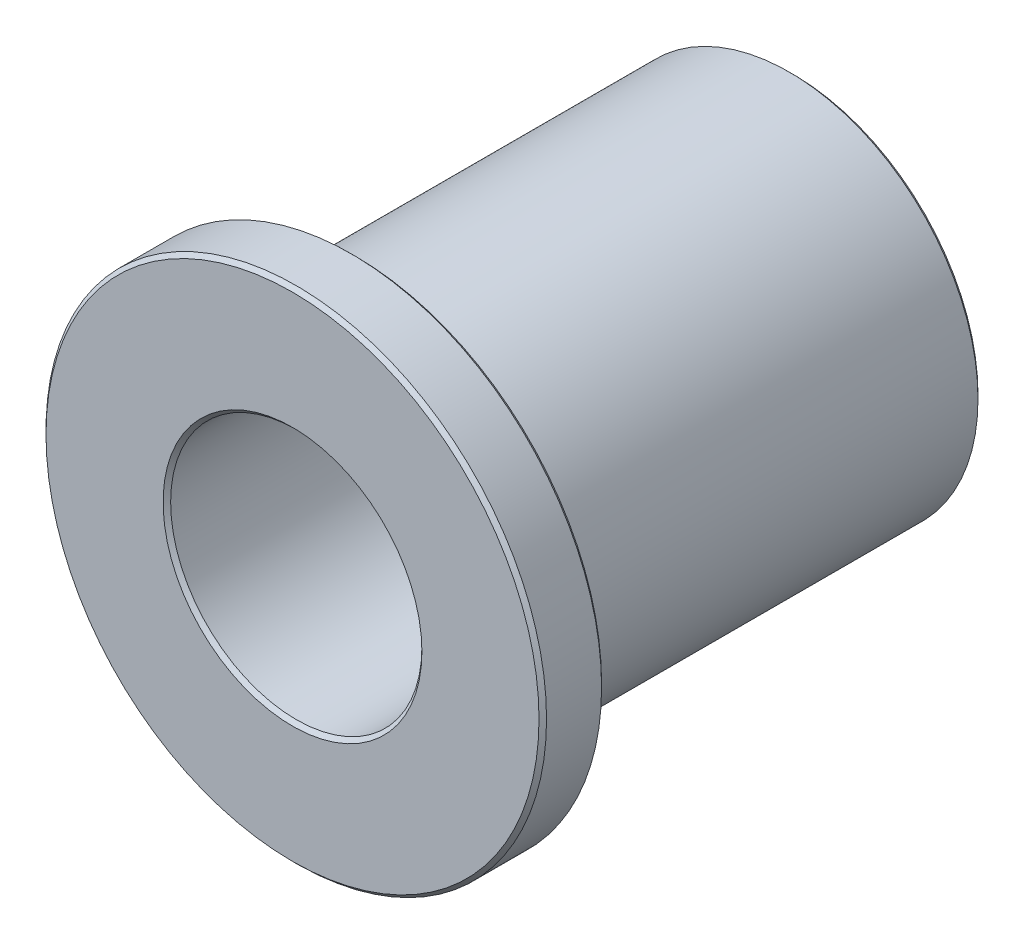
SolidWorks part; units mm, degrees
material "Brass"
ref_plane "Front" through (0, 0, 0) normal (0, 0, 1) x (1, 0, 0)
ref_plane "Top" through (0, 0, 0) normal (0, 1, 0) x (1, 0, 0)
ref_plane "Right" through (0, 0, 0) normal (1, 0, 0) x (0, 0, -1)
sketch "Sketch1" plane through (0, 0, 0) normal (0, 0, 1) x (1, 0, 0)
  circle A0 centre (0, 0) radius 3.1877
  circle A1 centre (0, 0) radius 4.7879
  circle A2 centre (0, 0) radius 6.35
  dimension "ID" = 6.3754
  dimension "OD" = 9.5758
  dimension "Flange OD" = 12.7
sketch "Sketch2" plane through (0, 0, 0) normal (1, 0, 0) x (0, 0, -1)
  line L0 (-6.35, -6.35) -> (6.35, -6.35) construction
  line L1 (0, 6.35) -> (0, -6.35) construction
  line L3 (-4.7625, 4.7879) -> (6.35, 4.7879) construction
  point P3 (0, -6.35)
  point P7 (0, 4.7879)
  point P9 (-4.7625, -6.35)
  point P10 (-6.35, 6.35)
  point P23 (0, 6.35)
  dimension "Flange Thickness" = 1.5875
  dimension "Length" = 12.7
sketch "Sketch3" plane through (0, 0, 0) normal (0, 0, 1) x (1, 0, 0)
  circle A0 centre (0, 0) radius 6.35 construction
  circle A1 centre (0, 0) radius 6.35
  circle A2 centre (0, 0) radius 3.1877 construction
  circle A3 centre (0, 0) radius 3.1877
extrude "Boss-Extrude1" add sketch "Sketch3" against normal up to vertex (-4.7625 mm away) from vertex at 6.35 starting at point (0, -6.35, 6.35)
sketch "Sketch4" plane through (0, 0, 0) normal (0, 0, 1) x (1, 0, 0)
  circle A0 centre (0, 0) radius 3.1877 construction
  circle A1 centre (0, 0) radius 4.7879 construction
  circle A2 centre (0, 0) radius 3.1877
  circle A3 centre (0, 0) radius 4.7879
extrude "Boss-Extrude2" add sketch "Sketch4" against normal up to vertex (6.35 mm away) from vertex at 4.7625 starting at point (0, -6.35, 4.7625)
chamfer "Chamfer1" distance 0.0956 angle 45 6 edges at (3.1877, 0, 6.35) (6.35, 0, 6.35) (6.35, 0, 4.7625) (4.7879, 0, 4.7625) (3.1877, 0, -6.35) (4.7879, 0, -6.35)
equation "\"D1@Chamfer1\"=\"ID@Sketch1\"*0.015"
